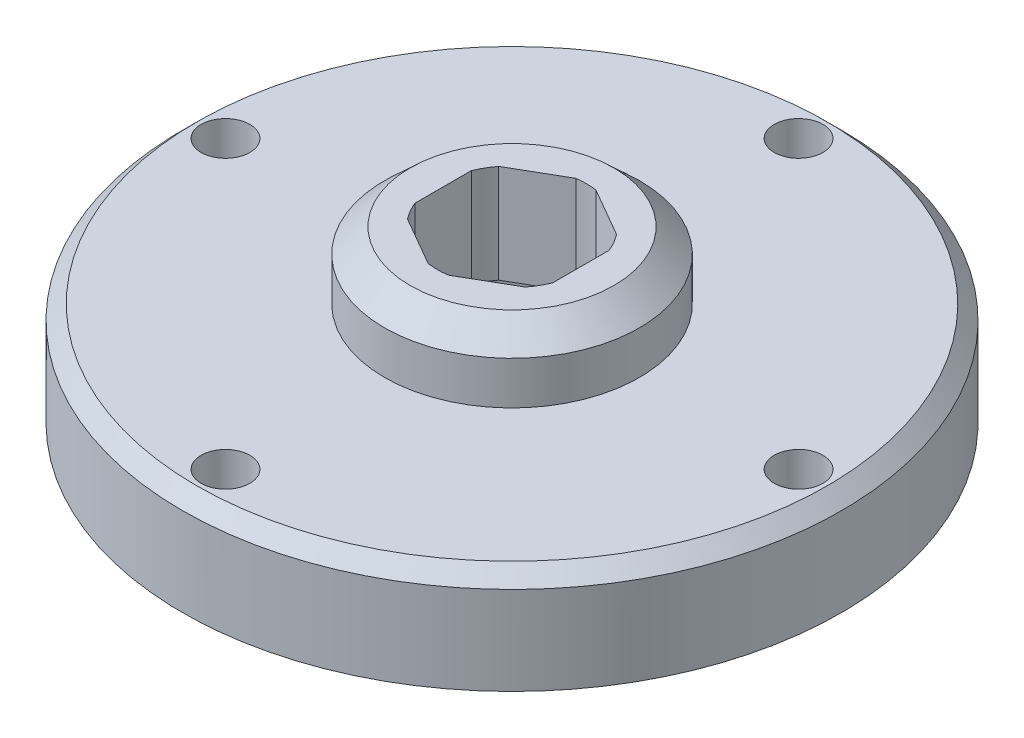
SolidWorks part; units mm, degrees
ref_plane "Front Plane" through (0, 0, 0) normal (0, 0, 1) x (1, 0, 0)
ref_plane "Top Plane" through (0, 0, 0) normal (0, 1, 0) x (1, 0, 0)
ref_plane "Right Plane" through (0, 0, 0) normal (1, 0, 0) x (0, 0, -1)
sketch "Sketch1" plane through (0, 0, 0) normal (0, 0, 1) x (1, 0, 0)
  line L0 (6.8, 0) -> (6.8, 4.953)
  line L1 (6.8, 4.953) -> (5.2, 4.953)
  line L2 (5.2, 4.953) -> (5.2, 11.829)
  line L3 (5.2, 11.829) -> (7.112, 11.829)
  line L5 (8.9, 7.1665) -> (23, 7.1665)
  line L6 (23, 7.1665) -> (23, 0)
  line L7 (23, 0) -> (6.8, 0)
  line L8 (7.112, 11.829) -> (8.9, 10.1665)
  line L9 (8.9, 10.1665) -> (8.9, 7.1665)
  line L10 (0, 0) -> (0, 16.4092) construction
  dimension "D1" = 6.8
  dimension "D2" = 23
  dimension "D3" = 4.953
  dimension "D4" = 8.9
  dimension "D5" = 11.829
  dimension "D6" = 7.1665
  dimension "D7" = 3
  dimension "D8" = 7.112
  dimension "D9" = 5.2
revolve "Revolve1" add sketch "Sketch1" angle 360 about L10
sketch "Sketch2" plane through (0, 0, 0) normal (0, 1, 0) x (1, 0, 0)
  circle A0 centre (0, 0) radius 20 construction
  point P3 (-20, 0)
  dimension "D1" = 40
hole_wizard "M3 Clearance Hole1" positions "Sketch2" profile "Sketch3" hole size "M3" standard "ANSI Metric" end condition through all
sketch "Sketch3" plane through (-20, 0, 0) normal (1, 0, 0) x (0, 0, -1)
  line L0 (0, 0) -> (0, 11.829)
  line L1 (0, 11.829) -> (1.7, 11.829)
  line L2 (1.7, 11.829) -> (1.7, 0)
  line L5 (1.7, 0) -> (0, 0)
  line L11 (0, -6.35) -> (0, 107.95) construction
  dimension "Thru Hole Dia." = 3.4
  dimension "Thru Hole Depth" = 11.829
pattern_circular "CirPattern1" count 4 over 360 about axis through (0, 0, 0) along (0, 1, 0) of "M3 Clearance Hole1"
sketch "Sketch4" plane through (0, 4.953, 0) normal (0, -1, 0) x (1, 0, 0)
  line L1 (4.8125, 2.7785) -> (0, 5.557)
  line L2 (0, 5.557) -> (-4.8125, 2.7785)
  line L3 (-4.8125, 2.7785) -> (-4.8125, -2.7785)
  line L4 (-4.8125, -2.7785) -> (0, -5.557)
  line L5 (0, -5.557) -> (4.8125, -2.7785)
  line L6 (4.8125, -2.7785) -> (4.8125, 2.7785)
  circle A0 centre (0, 0) radius 4.8125 construction
  circle A1 centre (0, 0) radius 5.2 construction
  circle A2 centre (0, 0) radius 5.2
  circle M9 centre (0, 0) radius 5.2
  dimension "D1" = 9.625
extrude "Boss-Extrude1" add sketch "Sketch4" against normal up to surface (6.876 mm away) contours L2 M9 | L3 M9 | L4 M9 | L5 M9 | L6 M9 | L1 M9 | A2
chamfer "Chamfer1" distance 0.75 angle 45 1 edges at (0, 0, -6.8)
chamfer "Chamfer2" distance 1 angle 45 1 edges at (0, 7.1665, -23)
